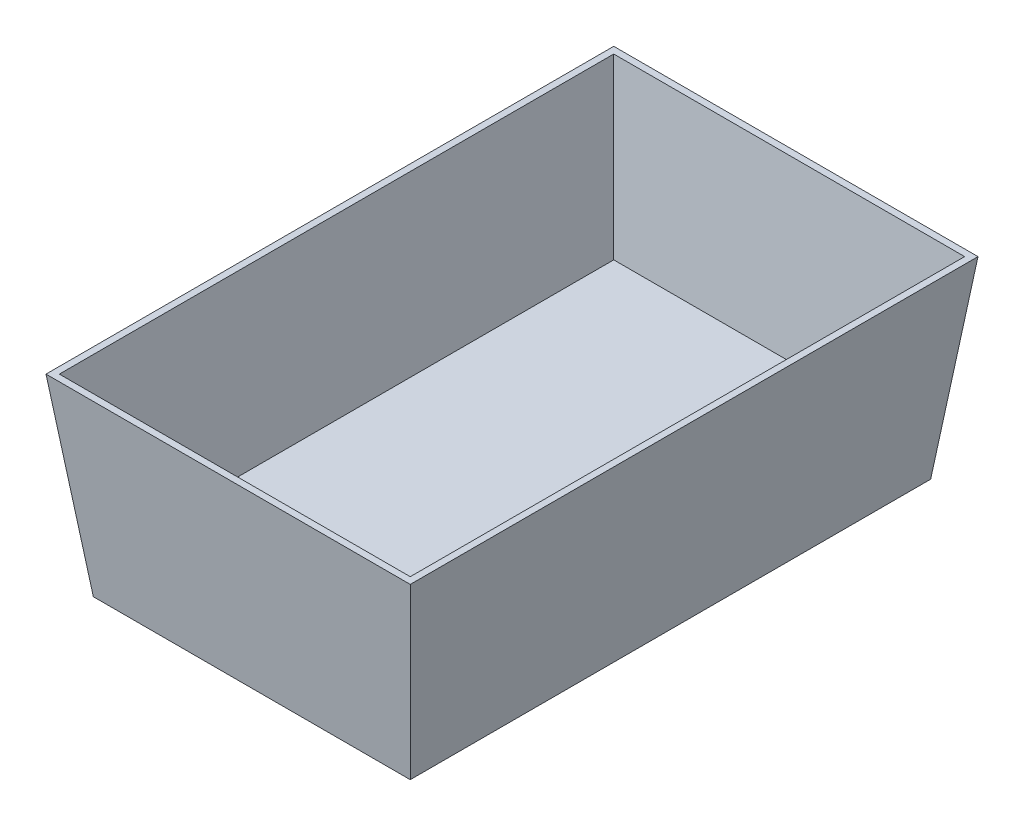
SolidWorks part; units mm, degrees
ref_plane "Спереди" through (0, 0, 0) normal (0, 0, 1) x (1, 0, 0)
ref_plane "Сверху" through (0, 0, 0) normal (0, 1, 0) x (1, 0, 0)
ref_plane "Справа" through (0, 0, 0) normal (1, 0, 0) x (0, 0, -1)
sketch "Эскиз1" plane through (0, 0, 0) normal (0, 1, 0) x (1, 0, 0)
  line L1 (-227.8958, 294.3477) -> (-702.8958, 294.3477)
  line L2 (-227.8958, 294.3477) -> (-227.8958, -485.6523)
  line L3 (-227.8958, -485.6523) -> (-702.8958, -485.6523)
  line L4 (-702.8958, 294.3477) -> (-702.8958, -485.6523)
  dimension "D1" = 780
  dimension "D2" = 475
extrude "Бобышка-Вытянуть1" add sketch "Эскиз1" along normal blind 289 draft 7 draft outward yes
sketch "Эскиз2" plane through (0, 289, 0) normal (0, 1, 0) x (1, 0, 0)
  line L0 (-192.411, 329.8324) -> (-738.3805, 329.8324) construction
  line L1 (-728.3805, 319.8324) -> (-202.411, 319.8324)
  line L2 (-728.3805, 319.8324) -> (-728.3805, -511.1371)
  line L3 (-728.3805, -511.1371) -> (-202.411, -511.1371)
  line L4 (-202.411, 319.8324) -> (-202.411, -511.1371)
  line L5 (-738.3805, 329.8324) -> (-738.3805, -521.1371) construction
  point P4 (-465.3958, 319.8324)
  point P7 (-465.3958, 329.8324)
  point P8 (-728.3805, -95.6523)
  point P11 (-738.3805, -95.6523)
  dimension "D1" = 10
  dimension "D2" = 10
extrude "Вырез-Вытянуть1" cut sketch "Эскиз2" against normal blind 238 draft 7
